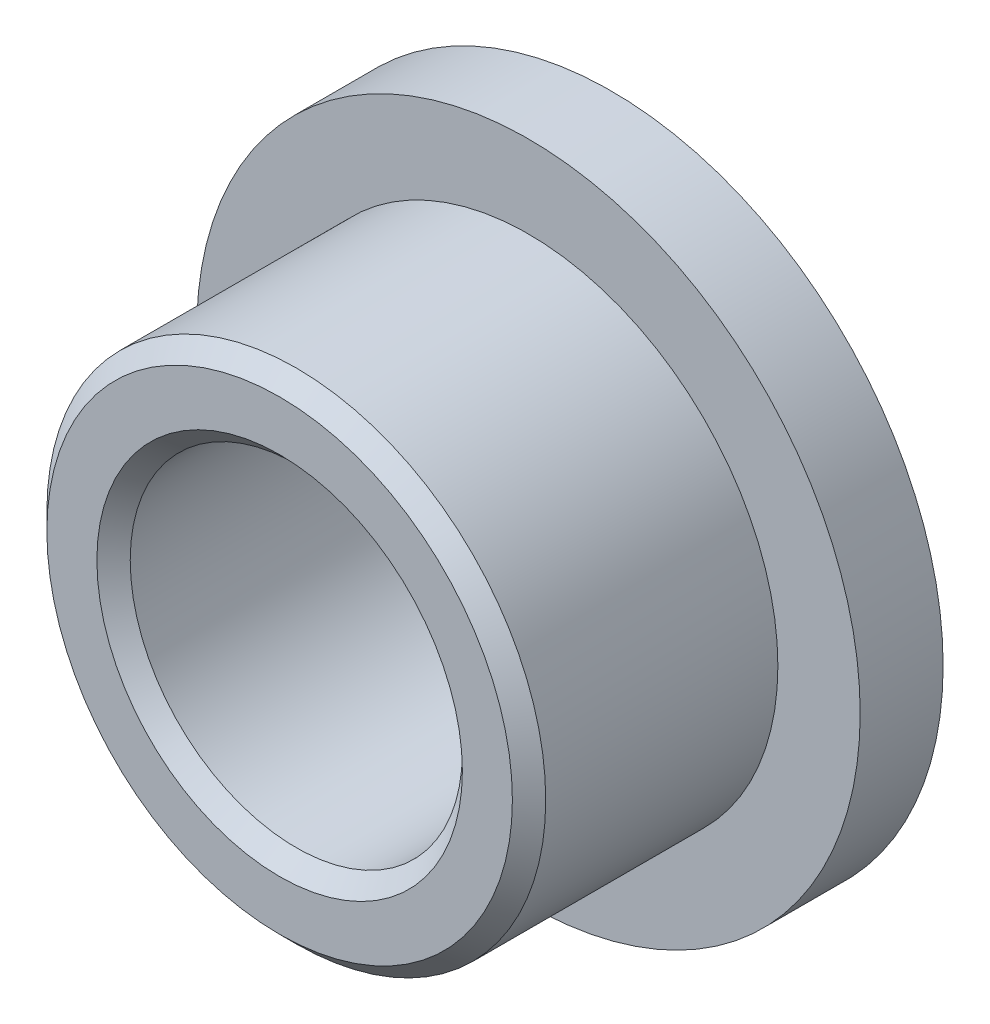
SolidWorks part; units mm, degrees
ref_plane "Front Plane" through (0, 0, 0) normal (0, 0, 1) x (1, 0, 0)
ref_plane "Top Plane" through (0, 0, 0) normal (0, 1, 0) x (1, 0, 0)
ref_plane "Right Plane" through (0, 0, 0) normal (1, 0, 0) x (0, 0, -1)
sketch "Sketch1" plane through (0, 0, 0) normal (1, 0, 0) x (0, 0, -1)
  line L0 (-4, 0) -> (4, 0) construction
  line L1 (4, 4.005) -> (4, -4.005) construction
  line L2 (4, 4.005) -> (-4, 4.005)
  line L3 (-4, 4.005) -> (-4, 6.015)
  line L4 (-4, 6.015) -> (2, 6.015)
  line L5 (2, 6.015) -> (2, 8)
  line L6 (2, 8) -> (4, 8)
  line L7 (4, 8) -> (4, 4.005)
  point P4 (0, 0)
  point P8 (4, 0)
  dimension "Flange OD" = 16
  dimension "OD" = 12.03
  dimension "ID" = 8.01
  dimension "Flange Thickness" = 2
  dimension "Length" = 8
sketch "Sketch2" plane through (0, 0, 0) normal (1, 0, 0) x (0, 0, -1)
  line L6 (-4, 4.005) -> (4, 4.005)
  line L7 (-4, 6.015) -> (-4, 4.005)
  line L8 (2, 6.015) -> (-4, 6.015)
  line L9 (2, 8) -> (2, 6.015)
  line L10 (4, 8) -> (2, 8)
  line L11 (4, 4.005) -> (4, 8)
  line L12 (-4, 4.005) -> (4, 4.005)
  line L13 (-4, 6.015) -> (-4, 4.005)
  line L14 (2, 6.015) -> (-4, 6.015)
  line L15 (2, 8) -> (2, 6.015)
  line L16 (4, 8) -> (2, 8)
  line L17 (4, 4.005) -> (4, 8)
  dimension "D1" = 0
revolve "Revolve1" add sketch "Sketch2" angle 360 about L0
sketch "Sketch3" plane through (0, 0, 0) normal (0, 0, 1) x (1, 0, 0)
  circle A0 centre (0, 0) radius 4.005
  circle A1 centre (0, 0) radius 6.015
  dimension "OD" = 12.03
  dimension "ID" = 8.01
chamfer "Chamfer1" distance 0.402 angle 45 3 edges at (4.005, 0, 4) (4.005, 0, -4) (6.015, 0, 4)
equation "\"D1@Chamfer1\"=(\"OD@Sketch1\"-\"ID@Sketch1\")*.1"
